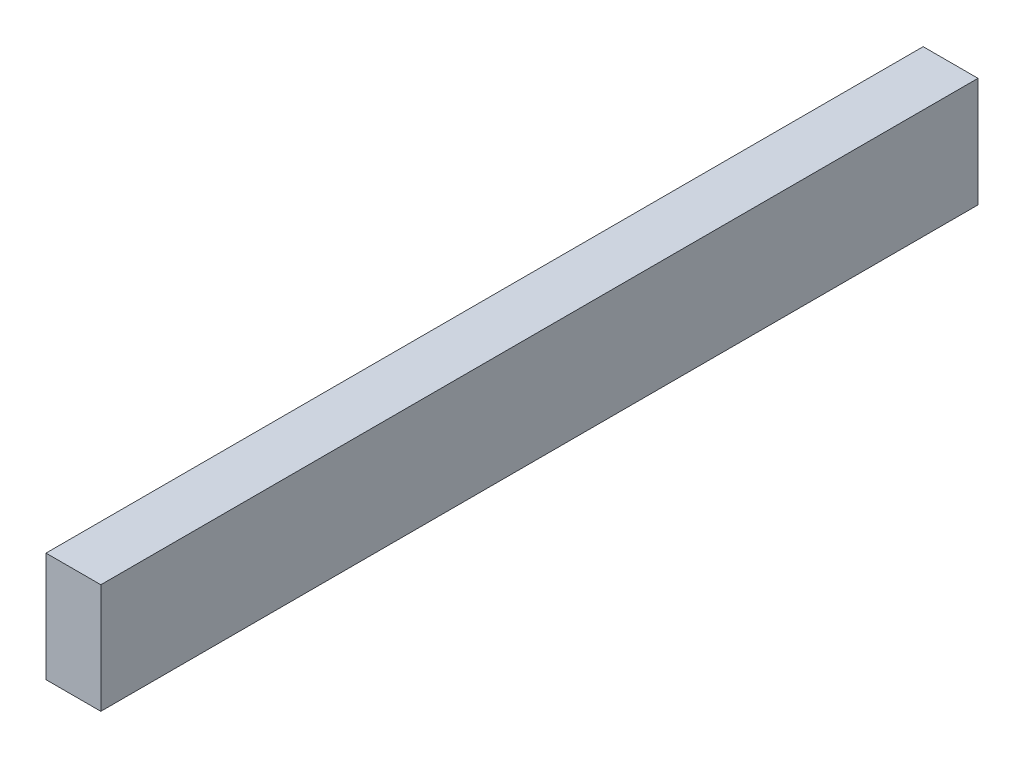
SolidWorks part; units mm, degrees
ref_plane "Front Plane" through (0, 0, 0) normal (0, 0, 1) x (1, 0, 0)
ref_plane "Top Plane" through (0, 0, 0) normal (0, 1, 0) x (1, 0, 0)
ref_plane "Right Plane" through (0, 0, 0) normal (1, 0, 0) x (0, 0, -1)
sketch "Sketch1" plane through (0, 0, 0) normal (0, 0, 1) x (1, 0, 0)
  line L1 (-25.4, -50.8) -> (25.4, -50.8)
  line L2 (-25.4, -50.8) -> (-25.4, 50.8)
  line L3 (-25.4, 50.8) -> (25.4, 50.8)
  line L4 (25.4, -50.8) -> (25.4, 50.8)
  line L5 (-25.4, -50.8) -> (25.4, 50.8) construction
  line L6 (-25.4, 50.8) -> (25.4, -50.8) construction
  point P0 (0, 0)
  dimension "D1" = 50.8
  dimension "D2" = 101.6
extrude "Boss-Extrude1" add sketch "Sketch1" along normal blind 812.8
ref_plane "Plane1" through (0, 0, 0) normal (1, 0, 0) x (0, 0, -1)
